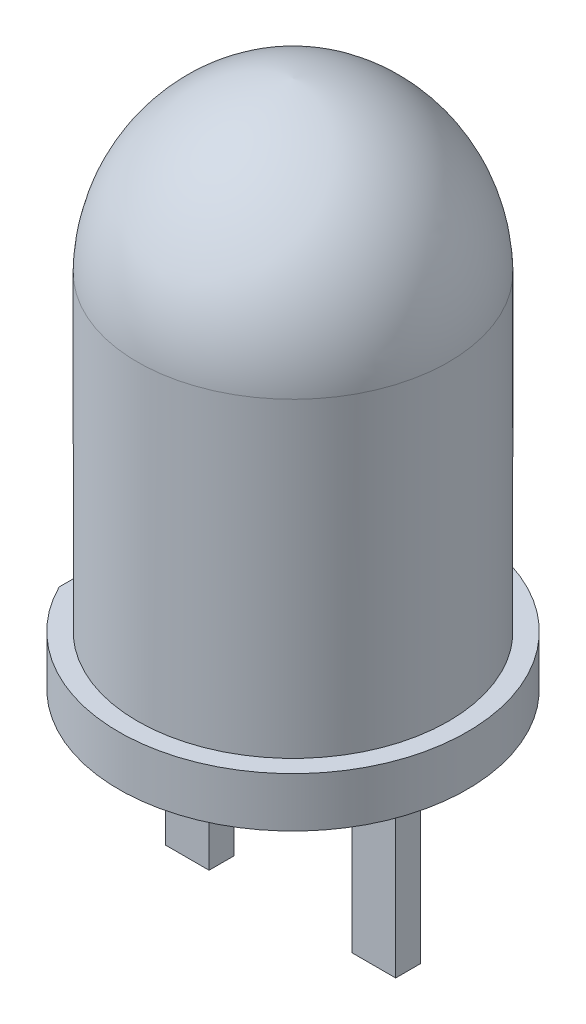
SolidWorks part; units mm, degrees
ref_plane "Alzado" through (0, 0, 0) normal (0, 0, 1) x (1, 0, 0)
ref_plane "Planta" through (0, 0, 0) normal (0, 1, 0) x (1, 0, 0)
ref_plane "Vista lateral" through (0, 0, 0) normal (1, 0, 0) x (0, 0, -1)
sketch "Croquis1" plane through (0, 0, 0) normal (0, 0, 1) x (1, 0, 0)
  line L0 (0, 0) -> (0, 8.5)
  line L1 (0, 0) -> (2.8, 0)
  line L2 (2.8, 0) -> (2.8, 0.8)
  line L3 (2.8, 0.8) -> (2.5, 0.8)
  line L4 (2.5, 0.8) -> (2.5, 5.8)
  arc A0 (0, 8.5) -> (2.5, 5.8) centre (-0.2497, 5.7614) cw
  dimension "D6" = 2.75
  dimension "D1" = 8.5
  dimension "D2" = 2.8
  dimension "D3" = 0.8
  dimension "D4" = 2.5
  dimension "D5" = 5
revolve "Revolución1" add sketch "Croquis1" angle 360 about L0
sketch "Croquis2" plane through (0, 0.8, 0) normal (0, 1, 0) x (1, 0, 0)
  line L0 (-2.5, 0) -> (-3.8586, 0) construction
  line L1 (-2.5, -1.261) -> (-2.5, 1.261)
  circle A0 centre (0, 0) radius 2.5 construction
  circle A1 centre (0, 0) radius 2.8 construction
  circle A2 centre (0, 0) radius 2.8
  arc A3 (-2.5, 1.261) -> (-2.5, -1.261) centre (0, 0) ccw
  circle M6 centre (0, 0) radius 2.8
extrude "Cortar-Extruir1" cut sketch "Croquis2" against normal blind 10 contours L0 L1 M6 | L1 L0 A3
sketch "Croquis3" plane through (0, 0, 0) normal (0, -1, 0) x (1, 0, 0)
  line L0 (0, 0) -> (-2.5, 0)
  line L1 (-2.5, -1.261) -> (-2.5, 1.261) construction
  line L2 (-1.85, 0.2) -> (-1.15, 0.2)
  line L3 (-1.85, 0.2) -> (-1.85, -0.2)
  line L4 (-1.85, -0.2) -> (-1.15, -0.2)
  line L5 (-1.15, 0.2) -> (-1.15, -0.2)
  line L6 (-1.85, 0.2) -> (-1.15, -0.2) construction
  line L7 (-1.85, -0.2) -> (-1.15, 0.2) construction
  line L8 (0, 0) -> (0, 1.6334) construction
  line L9 (1.85, 0.2) -> (1.85, -0.2)
  line L10 (1.85, 0.2) -> (1.15, 0.2)
  line L11 (1.85, -0.2) -> (1.15, -0.2)
  line L12 (1.15, 0.2) -> (1.15, -0.2)
  point P4 (-1.5, 0)
  dimension "D1" = 1
  dimension "D2" = 0.4
  dimension "D3" = 0.7
extrude "Saliente-Extruir1" add sketch "Croquis3" along normal blind 3 contours L10 L12 L11 L9 | L5 L0 L3 L4
